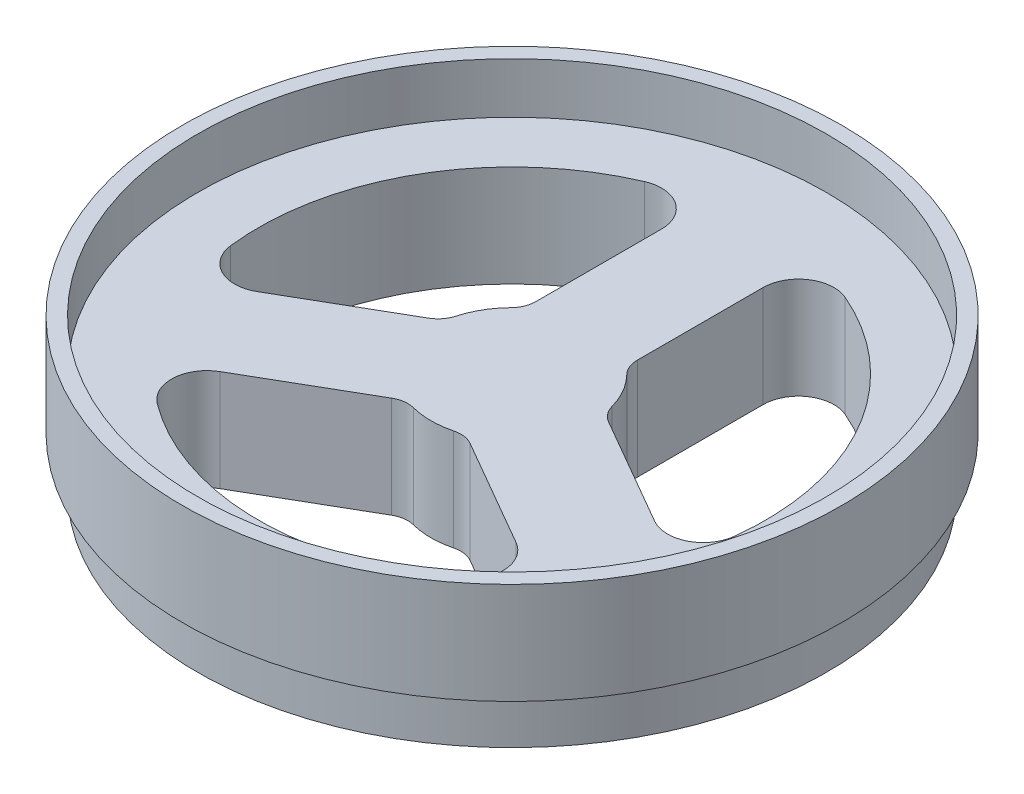
SolidWorks part; units mm, degrees
material "HYPALON"
ref_plane "Front Plane" through (0, 0, 0) normal (0, 0, 1) x (1, 0, 0)
ref_plane "Top Plane" through (0, 0, 0) normal (0, 1, 0) x (1, 0, 0)
ref_plane "Right Plane" through (0, 0, 0) normal (1, 0, 0) x (0, 0, -1)
sketch "Sketch1" plane through (0, 0, 0) normal (0, 0, 1) x (1, 0, 0)
  line L0 (0, 0) -> (0, 22.2877) construction
  line L1 (0, 0) -> (-62, 0)
  line L2 (-62, 0) -> (-62, 10)
  line L3 (-62, 10) -> (-65, 10)
  line L4 (-65, 10) -> (-65, 30)
  line L5 (-65, 30) -> (-62, 30)
  line L6 (-62, 30) -> (-62, 20)
  line L7 (-62, 20) -> (0, 20)
  line L8 (0, 20) -> (0, 0)
  point P3 (-62, 25)
  dimension "D1" = 20
  dimension "D2" = 10
  dimension "D3" = 10
  dimension "D4" = 3
  dimension "D5" = 65
  dimension "D6" = 3
revolve "Revolve1" add sketch "Sketch1" angle 360 about L0
sketch "Szkic1" plane through (0, 0, 0) normal (0, 1, 0) x (1, 0, 0)
  line L0 (0, 0) -> (-10, 0)
  line L1 (-10, 0) -> (0, 0)
  line L2 (0, 0) -> (10, 0)
  line L3 (-10, 0) -> (-10, 12.49)
  line L4 (10, 0) -> (10, 12.49)
  line L5 (5.8167, -14.9053) -> (37.4264, -33.1552)
  line L6 (-10, 12.49) -> (-10, 48.9898)
  line L7 (10, 12.49) -> (10, 48.9898)
  line L8 (15.8167, 2.4153) -> (47.4264, -15.8346)
  line L9 (-15.8167, 2.4153) -> (-47.4264, -15.8346)
  line L10 (-5.8167, -14.9053) -> (-37.4264, -33.1552)
  circle A0 centre (0, 0) radius 64
  circle A1 centre (0, 0) radius 50
  circle A2 centre (0, 0) radius 16
  point P22 (0, 0)
  dimension "D1" = 128
  dimension "D2" = 100
  dimension "D5" = 32
  dimension "D3" = 10
  dimension "D4" = 10
  dimension "D6" = 3
sketch "Szkic2" plane through (0, 0, 0) normal (0, 1, 0) x (1, 0, 0)
  circle A0 centre (0, 0) radius 35
  circle A1 centre (0, 0) radius 63
  dimension "D1" = 126
  dimension "D2" = 70
extrude "Cut-Extrude1" cut sketch "Szkic1" along normal up to surface (20 mm away) contours A2 L6 A1 L9 | A2 L8 A1 L7 | A2 L10 A1 L5 up to face at (0, 20, -62)
fillet "Fillet1" radius 5 6 edges at (-15.8167, 10, -2.4153) (-10, 10, -12.49) (10, 10, -12.49) (15.8167, 10, -2.4153) (5.8167, 10, 14.9053) (-5.8167, 10, 14.9053)
fillet "Fillet2" radius 7 6 edges at (37.4264, 10, 33.1552) (47.4264, 10, 15.8346) (10, 10, -48.9898) (-10, 10, -48.9898) (-47.4264, 10, 15.8346) (-37.4264, 10, 33.1552)
